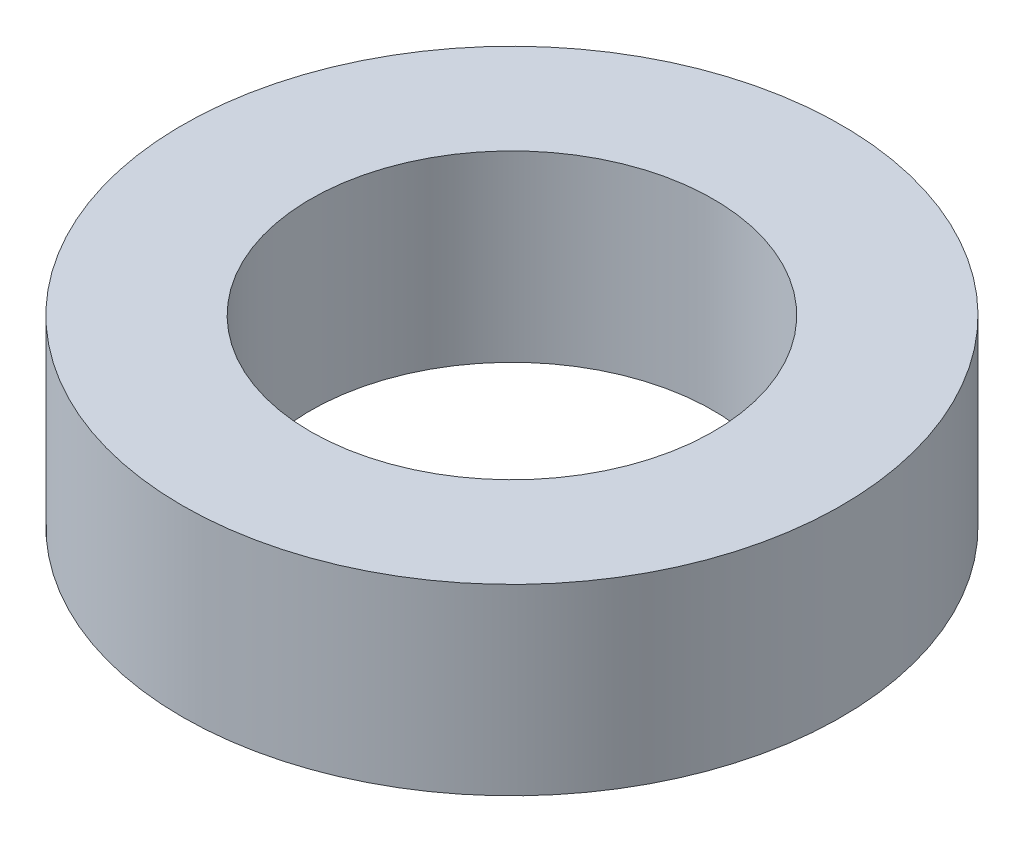
SolidWorks part; units mm, degrees
material "AISI 1020"
ref_plane "Front Plane" through (0, 0, 0) normal (0, 0, 1) x (1, 0, 0)
ref_plane "Top Plane" through (0, 0, 0) normal (0, 1, 0) x (1, 0, 0)
ref_plane "Right Plane" through (0, 0, 0) normal (1, 0, 0) x (0, 0, -1)
sketch "Sketch1" plane through (0, 0, 0) normal (0, 1, 0) x (1, 0, 0)
  circle A0 centre (0, 0) radius 18
  dimension "D1" = 36
extrude "Boss-Extrude1" add sketch "Sketch1" along normal mid plane 10
hole_wizard "M24x2.0 Tapped Hole1" positions "Sketch2" profile "Sketch3" tap size "M24x2.0" standard "ANSI Metric" end condition through all
sketch "Sketch2" plane through (0, 5, 0) normal (0, 1, 0) x (1, 0, 0)
  point P0 (0, 0)
sketch "Sketch3" plane through (0, 5, 0) normal (1, 0, 0) x (0, 0, 1)
  line L0 (0, 0) -> (0, 10)
  line L1 (0, 10) -> (11, 10)
  line L2 (11, 10) -> (11, 0)
  line L5 (11, 0) -> (0, 0)
  line L11 (0, -6.35) -> (0, 107.95) construction
  dimension "Thru Tap Drill Dia." = 22
  dimension "Thru Tap Drill Depth" = 10
cosmetic thread "Hole Thread1" parameters "D2"=24
